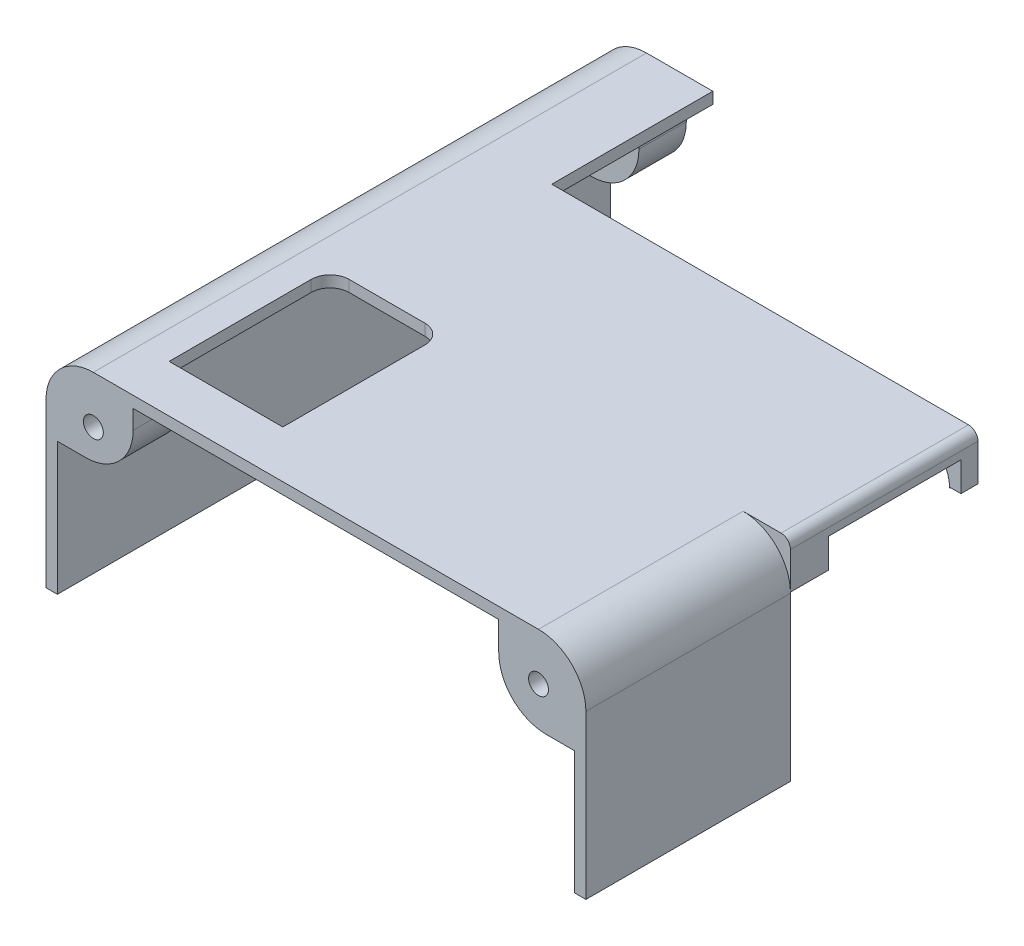
SolidWorks part; units mm, degrees
ref_plane "Front Plane" through (0, 0, 0) normal (0, 0, 1) x (1, 0, 0)
ref_plane "Top Plane" through (0, 0, 0) normal (0, 1, 0) x (1, 0, 0)
ref_plane "Right Plane" through (0, 0, 0) normal (1, 0, 0) x (0, 0, -1)
sketch "Sketch1" plane through (0, 0, 0) normal (0, 0, 1) x (1, 0, 0)
  line L1 (-28.7269, 17.6821) -> (28.2731, 17.6821)
  line L2 (-28.7269, 17.6821) -> (-28.7269, -4.9179)
  line L3 (-28.7269, -4.9179) -> (28.2731, -4.9179)
  line L4 (28.2731, 17.6821) -> (28.2731, -4.9179)
  dimension "D1" = 22.6
  dimension "D2" = 57
extrude "Boss-Extrude1" add sketch "Sketch1" along normal blind 58.4
fillet "Fillet1" radius 5 2 edges at (28.2731, 17.6821, 29.2) (-28.7269, 17.6821, 29.2)
sketch "Sketch2" plane through (0, 0, 58.4) normal (0, 0, 1) x (1, 0, 0)
  line L3 (-27.5269, -4.9179) -> (27.0731, -4.9179)
  line L6 (-27.5269, 12.6821) -> (-27.5269, -4.9179)
  line L7 (27.0731, -4.9179) -> (27.0731, 12.6821)
  line L8 (23.2731, 16.4821) -> (-23.7269, 16.4821)
  line L9 (-27.5269, 12.6821) -> (-27.5269, -4.9179)
  line L10 (27.0731, -4.9179) -> (27.0731, 12.6821)
  line L11 (23.2731, 16.4821) -> (-23.7269, 16.4821)
  arc A4 (-23.7269, 16.4821) -> (-27.5269, 12.6821) centre (-23.7269, 12.6821) ccw
  arc A5 (27.0731, 12.6821) -> (23.2731, 16.4821) centre (23.2731, 12.6821) ccw
  arc A6 (-23.7269, 16.4821) -> (-27.5269, 12.6821) centre (-23.7269, 12.6821) ccw
  arc A7 (27.0731, 12.6821) -> (23.2731, 16.4821) centre (23.2731, 12.6821) ccw
  dimension "D1" = 1.2
extrude "Cut-Extrude1" cut sketch "Sketch2" against normal up to surface (58.4 mm away) up to face at (-0.2269, 8.8273, 0)
sketch "Sketch3" plane through (28.2731, 0, 0) normal (1, 0, 0) x (0, 0, -1)
  line L6 (-58.4, -4.9179) -> (-58.4, 12.6821) construction
  line L7 (0, -4.9179) -> (-36.8, -4.9179)
  line L8 (0, -4.9179) -> (0, 12.7821)
  line L9 (0, 12.7821) -> (-36.8, 12.7821)
  line L10 (-36.8, -4.9179) -> (-36.8, 12.7821)
  dimension "D1" = 17.7
  dimension "D2" = 21.6
extrude "Cut-Extrude2" cut sketch "Sketch3" against normal up to surface (1.2 mm away) up to face at (27.0731, 3.8821, 29.2)
sketch "Sketch5" plane through (0, 17.6821, 0) normal (0, 1, 0) x (1, 0, 0)
  line L0 (23.2731, 0) -> (-23.7269, 0) construction
  line L1 (-16.7279, 0) -> (28.2721, 0)
  line L2 (-16.7279, 0) -> (-16.7279, -17)
  line L3 (-16.7279, -17) -> (28.2721, -17)
  line L4 (28.2721, 0) -> (28.2721, -17)
  line L5 (28.2721, 0) -> (28.2721, -36.8) construction
  dimension "D1" = 45
  dimension "D2" = 17
extrude "Cut-Extrude5" cut sketch "Sketch5" against normal through all contours L2 L3 L4 L1
sketch "Sketch6" plane through (0, 17.6821, 0) normal (0, 1, 0) x (1, 0, 0)
  line L1 (-20.7269, -36.4) -> (-8.7269, -36.4)
  line L2 (-20.7269, -36.4) -> (-20.7269, -53.4)
  line L3 (-20.7269, -53.4) -> (-8.7269, -53.4)
  line L4 (-8.7269, -36.4) -> (-8.7269, -53.4)
  line L5 (23.2731, -58.4) -> (-23.7269, -58.4) construction
  line L7 (-23.7269, 0) -> (-23.7269, -58.4) construction
  dimension "D1" = 12
  dimension "D2" = 17
  dimension "D3" = 5
  dimension "D4" = 3
extrude "Cut-Extrude6" cut sketch "Sketch6" against normal up to surface (1.2 mm away) up to face at (-5.7272, 16.4821, 25.1333)
fillet "Fillet3" radius 2 2 edges at (-20.7269, 17.0821, 36.4) (-8.7269, 17.0821, 36.4)
sketch "Sketch7" plane through (0, 0, 58.4) normal (0, 0, 1) x (1, 0, 0)
  line L0 (-27.5269, 9.4821) -> (-19.5269, 9.4821)
  line L1 (-27.5269, 12.6821) -> (-27.5269, -4.9179) construction
  line L2 (-19.5269, 9.4821) -> (-19.5269, 16.4821)
  line L3 (23.2731, 16.4821) -> (-23.7269, 16.4821) construction
  line L4 (-19.5269, 16.4821) -> (-23.7269, 16.4821)
  line L5 (-27.5269, 9.4821) -> (-27.5269, 12.6821)
  line L6 (19.0731, 16.4821) -> (19.0731, 8.4821)
  line L7 (19.0731, 8.4821) -> (27.0731, 8.4821)
  line L8 (27.0731, -4.9179) -> (27.0731, 12.6821) construction
  line L9 (19.0731, 16.4821) -> (23.2731, 16.4821)
  line L10 (27.0731, 8.4821) -> (27.0731, 12.6821)
  arc A0 (-23.7269, 16.4821) -> (-27.5269, 12.6821) centre (-23.7269, 12.6821) ccw
  arc A1 (27.0731, 12.6821) -> (23.2731, 16.4821) centre (23.2731, 12.6821) ccw
  circle A2 centre (-23.7269, 12.6821) radius 1.05
  circle A3 centre (23.2731, 12.6821) radius 1.05
  dimension "D5" = 2.1
  dimension "D6" = 2.1
  dimension "D1" = 8
  dimension "D2" = 7
  dimension "D3" = 8
  dimension "D4" = 8
extrude "Boss-Extrude2" add sketch "Sketch7" against normal blind 5
fillet "Fillet4" radius 5 2 edges at (19.0731, 8.4821, 55.9) (-19.5269, 9.4821, 55.9)
sketch "Sketch8" plane through (0, 0, 0) normal (0, 0, -1) x (-1, 0, 0)
  line L0 (19.5269, 16.4821) -> (19.5269, 8.4821)
  line L1 (23.7269, 16.4821) -> (16.7279, 16.4821) construction
  line L2 (19.5269, 8.4821) -> (27.5269, 8.4821)
  line L3 (27.5269, -4.9179) -> (27.5269, 12.6821) construction
  line L4 (19.5269, 16.4821) -> (23.7269, 16.4821)
  line L5 (27.5269, 8.4821) -> (27.5269, 12.6821)
  arc A0 (27.5269, 12.6821) -> (23.7269, 16.4821) centre (23.7269, 12.6821) ccw
  circle A1 centre (23.7269, 12.6821) radius 1.05
  dimension "D3" = 2.1
  dimension "D1" = 8
  dimension "D2" = 8
extrude "Boss-Extrude3" add sketch "Sketch8" against normal blind 5
fillet "Fillet5" radius 5 1 edges at (-19.5269, 8.4821, 2.5)
sketch "Sketch10" plane through (-28.7269, 0, 0) normal (-1, 0, 0) x (0, 0, 1)
  line L0 (0, 12.6821) -> (0, -4.9179) construction
  line L1 (0, -2.7179) -> (9.1, -2.7179)
  line L2 (0, -2.7179) -> (0, 3.2821)
  line L3 (0, 3.2821) -> (9.1, 3.2821)
  line L4 (9.1, -2.7179) -> (9.1, 3.2821)
  line L5 (58.4, -4.9179) -> (0, -4.9179) construction
  dimension "D1" = 2.2
  dimension "D2" = 9.1
  dimension "D3" = 6
extrude "Boss-Extrude4" add sketch "Sketch10" along normal blind 6
sketch "Sketch11" plane through (-34.7269, 0, 0) normal (-1, 0, 0) x (0, 0, 1)
  line L1 (2.05, -4.9179) -> (7.05, -4.9179)
  line L2 (2.05, -4.9179) -> (2.05, 0.0821)
  line L3 (2.05, 0.0821) -> (7.05, 0.0821)
  line L4 (7.05, -4.9179) -> (7.05, 0.0821)
  line L6 (58.4, -4.9179) -> (0, -4.9179) construction
  line L7 (0, -2.7179) -> (9.1, -2.7179) construction
  dimension "D1" = 5
  dimension "D2" = 2.8
extrude "Cut-Extrude8" cut sketch "Sketch11" against normal up to surface (7.2 mm away) up to face at (-27.5269, 6.4321, 29.2)
fillet "Fillet6" radius 3 2 edges at (-31.7269, 3.2821, 0) (-31.7269, 3.2821, 9.1)
fillet "Fillet7" radius 3 5 edges at (-34.7269, -1.2179, 9.1) (-34.7269, 2.4034, 8.2213) (-34.7269, -1.2179, 0) (-34.7269, 2.4034, 0.8787) (-34.7269, 3.2821, 4.55)
fillet "Fillet8" radius 1 2 edges at (-31.0497, 0.0821, 7.05) (-31.0497, 0.0821, 2.05)
sketch "Sketch12" plane through (0, 0, 58.4) normal (0, 0, 1) x (1, 0, 0)
  line L0 (28.2731, -4.9179) -> (28.2731, 12.6821) construction
  line L1 (-28.7269, -4.9179) -> (28.2731, -4.9179)
  line L2 (-28.7269, -4.9179) -> (-28.7269, -4.5179)
  line L3 (-28.7269, -4.5179) -> (28.2731, -4.5179)
  line L4 (28.2731, -4.9179) -> (28.2731, -4.5179)
  dimension "D1" = 0.4
extrude "Cut-Extrude9" cut sketch "Sketch12" against normal through all
sketch "Sketch15" plane through (0, 0, 17) normal (0, 0, -1) x (-1, 0, 0)
  line L1 (-28.2721, 12.7821) -> (-27.2731, 12.7821)
  line L2 (-28.2721, 12.7821) -> (-28.2721, 17.6821)
  line L3 (-28.2721, 17.6821) -> (-23.2731, 17.6821)
  line L4 (-23.2731, 16.7821) -> (-23.2731, 17.6821)
  arc A0 (-23.2731, 16.7821) -> (-27.2731, 12.7821) centre (-23.2731, 12.7821) ccw
  dimension "D1" = 8
extrude "Boss-Extrude5" add sketch "Sketch15" against normal up to surface (19.8 mm away) up to face at (27.673, 6.9821, 36.8)
sketch "Sketch4" plane through (28.2731, 0, 0) normal (1, 0, 0) x (0, 0, -1)
  line L0 (-36.8, 12.6821) -> (-58.4, 12.6821) construction
  line L1 (-32.8, 15.8821) -> (-18.8, 15.8821)
  line L2 (-32.8, 15.8821) -> (-32.8, 12.6821)
  line L3 (-32.8, 12.6821) -> (-18.8, 12.6821)
  line L4 (-18.8, 15.8821) -> (-18.8, 12.6821)
  line L5 (-36.8, 12.6821) -> (-36.8, -4.5179) construction
  dimension "D1" = 4
  dimension "D2" = 14
  dimension "D3" = 3.2
extrude "Cut-Extrude3" cut sketch "Sketch4" against normal blind 5
fillet "Fillet9" radius 1 1 edges at (28.2721, 17.6821, 26.9)
